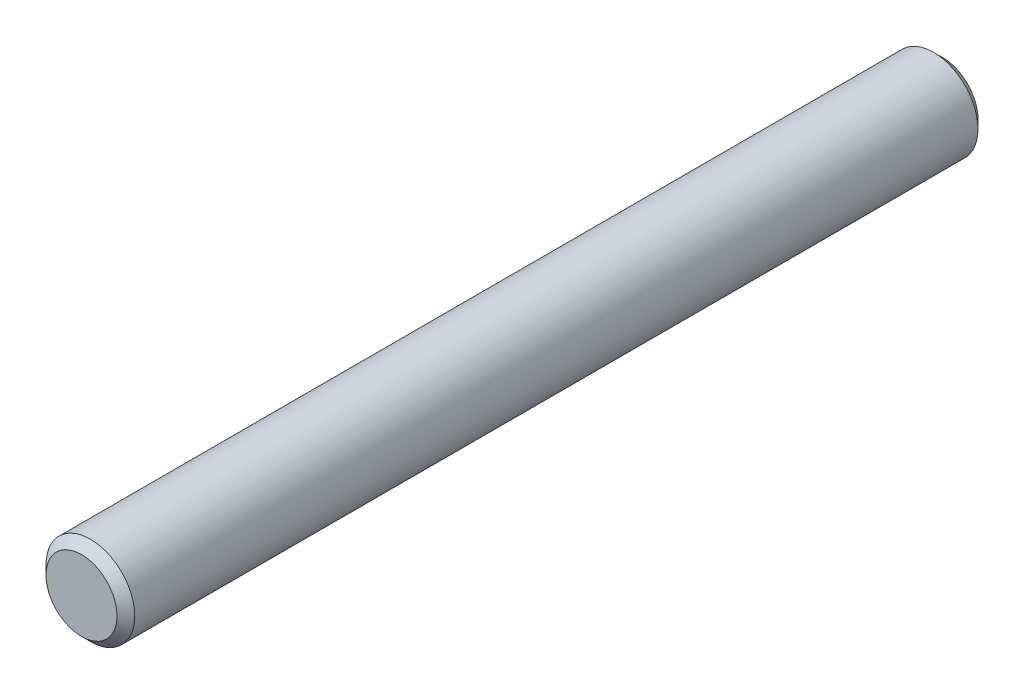
SolidWorks part; units mm, degrees
ref_plane "Front Plane" through (0, 0, 0) normal (0, 0, 1) x (1, 0, 0)
ref_plane "Top Plane" through (0, 0, 0) normal (0, 1, 0) x (1, 0, 0)
ref_plane "Right Plane" through (0, 0, 0) normal (1, 0, 0) x (0, 0, -1)
sketch "Sketch1" plane through (0, 0, 0) normal (1, 0, 0) x (0, 0, -1)
  line L0 (-5.6542, 0) -> (6.1308, 0) construction
  line L2 (0, 0) -> (9.7, 0)
  line L3 (0, 0) -> (0, 0.5)
  line L4 (0, 0.5) -> (9.7, 0.5)
  line L5 (9.7, 0) -> (9.7, 0.5)
  dimension "D1" = 1
  dimension "D2" = 9.7
revolve "Revolve1" add sketch "Sketch1" angle 360 about L0
chamfer "Chamfer1" distance 0.1 angle 45 2 edges at (0.5, 0, -9.7) (0.5, 0, 0)
